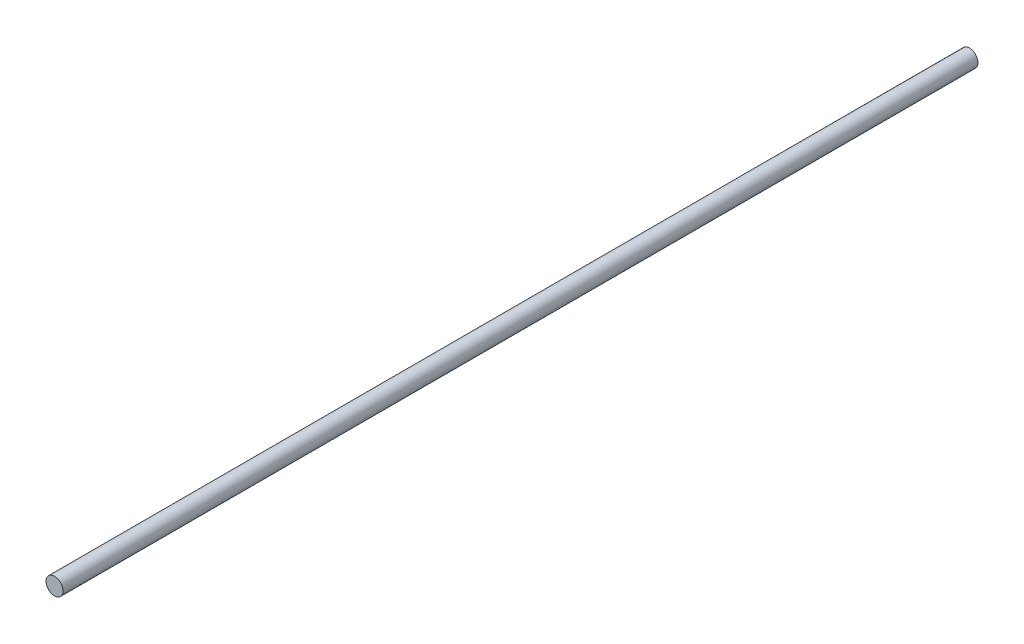
SolidWorks part; units mm, degrees
ref_plane "Front Plane" through (0, 0, 0) normal (0, 0, 1) x (1, 0, 0)
ref_plane "Top Plane" through (0, 0, 0) normal (0, 1, 0) x (1, 0, 0)
ref_plane "Right Plane" through (0, 0, 0) normal (1, 0, 0) x (0, 0, -1)
sketch "Sketch1" plane through (0, 0, 0) normal (0, 0, 1) x (1, 0, 0)
  circle A0 centre (0, 0) radius 4
  dimension "D1" = 8
extrude "Boss-Extrude1" add sketch "Sketch1" along normal blind 430
